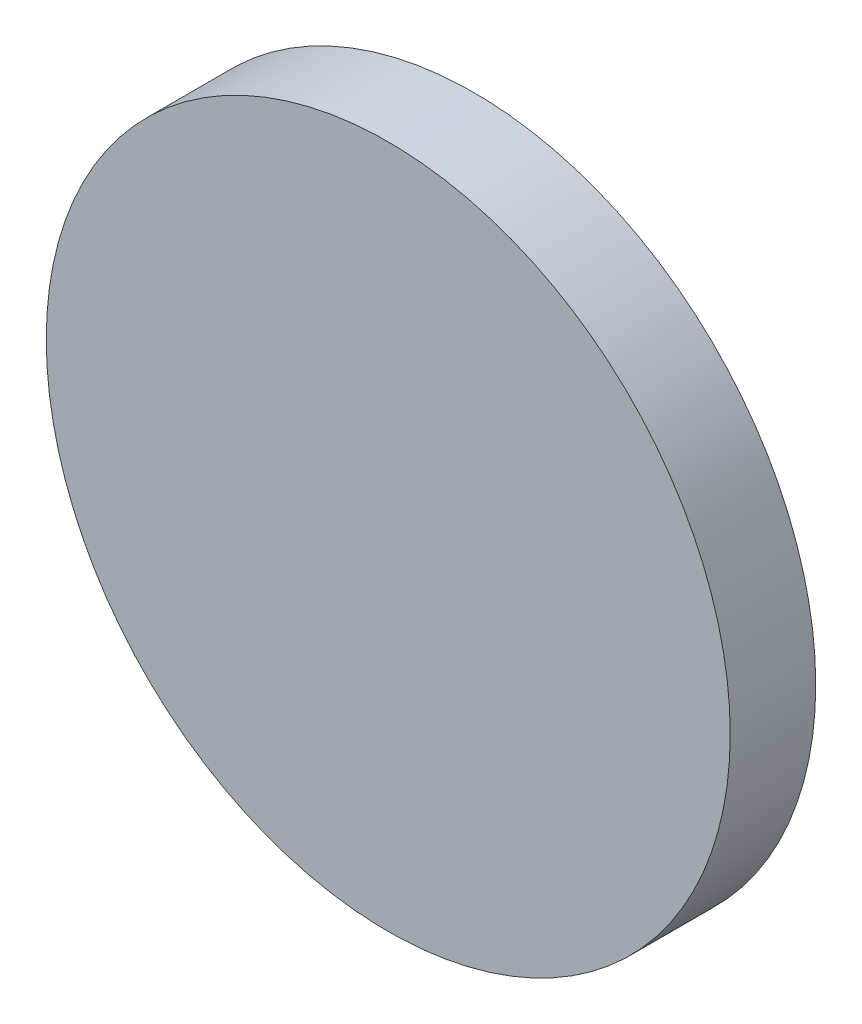
SolidWorks part; units mm, degrees
material "Silicon"
ref_plane "Front Plane" through (0, 0, 0) normal (0, 0, 1) x (1, 0, 0)
ref_plane "Top Plane" through (0, 0, 0) normal (0, 1, 0) x (1, 0, 0)
ref_plane "Right Plane" through (0, 0, 0) normal (1, 0, 0) x (0, 0, -1)
sketch "Sketch1" plane through (0, 0, 0) normal (0, 0, 1) x (1, 0, 0)
  circle A0 centre (0, 0) radius 4
  dimension "D1" = 8
extrude "Boss-Extrude1" add sketch "Sketch1" against normal blind 1
